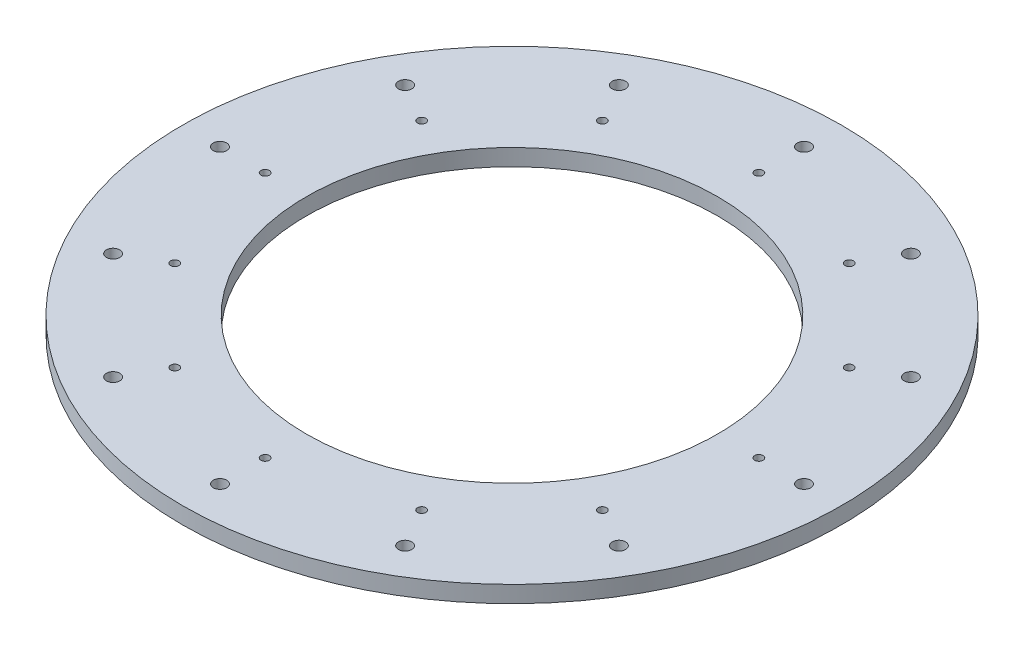
SolidWorks part; units mm, degrees
ref_plane "Ebene vorne" through (0, 0, 0) normal (0, 0, 1) x (1, 0, 0)
ref_plane "Ebene oben" through (0, 0, 0) normal (0, 1, 0) x (1, 0, 0)
ref_plane "Ebene rechts" through (0, 0, 0) normal (1, 0, 0) x (0, 0, -1)
sketch "Sketch1" plane through (0, 0, 0) normal (0, 1, 0) x (1, 0, 0)
  circle A0 centre (0, 59.18) radius 1
  circle A1 centre (29.59, 51.2514) radius 1
  circle A2 centre (51.2514, 29.59) radius 1
  circle A3 centre (59.18, 0) radius 1
  circle A4 centre (51.2514, -29.59) radius 1
  circle A5 centre (29.59, -51.2514) radius 1
  circle A6 centre (0, -59.18) radius 1
  circle A7 centre (-29.59, -51.2514) radius 1
  circle A8 centre (-51.2514, -29.59) radius 1
  circle A9 centre (-59.18, 0) radius 1
  circle A10 centre (-51.2514, 29.59) radius 1
  circle A11 centre (-29.59, 51.2514) radius 1
  circle A12 centre (0, 0) radius 79
  circle A13 centre (0, 0) radius 49.3
  circle A14 centre (0, 70) radius 1.6
  circle A15 centre (35, 60.6218) radius 1.6
  circle A16 centre (60.6218, 35) radius 1.6
  circle A17 centre (70, 0) radius 1.6
  circle A18 centre (60.6218, -35) radius 1.6
  circle A19 centre (35, -60.6218) radius 1.6
  circle A20 centre (0, -70) radius 1.6
  circle A21 centre (-35, -60.6218) radius 1.6
  circle A22 centre (-60.6218, -35) radius 1.6
  circle A23 centre (-70, 0) radius 1.6
  circle A24 centre (-60.6218, 35) radius 1.6
  circle A25 centre (-35, 60.6218) radius 1.6
  point P27 (0, 0)
  point P31 (0, 0)
  point P56 (0, 0)
  dimension "D1" = 2
  dimension "D3" = 118.36
  dimension "D4" = 158
  dimension "D5" = 98.6
  dimension "D8" = 3.2
  dimension "D7" = 140
  dimension "D2" = 12
  dimension "D6" = 12
extrude "Boss-Extrude1" add sketch "Sketch1" along normal blind 4
